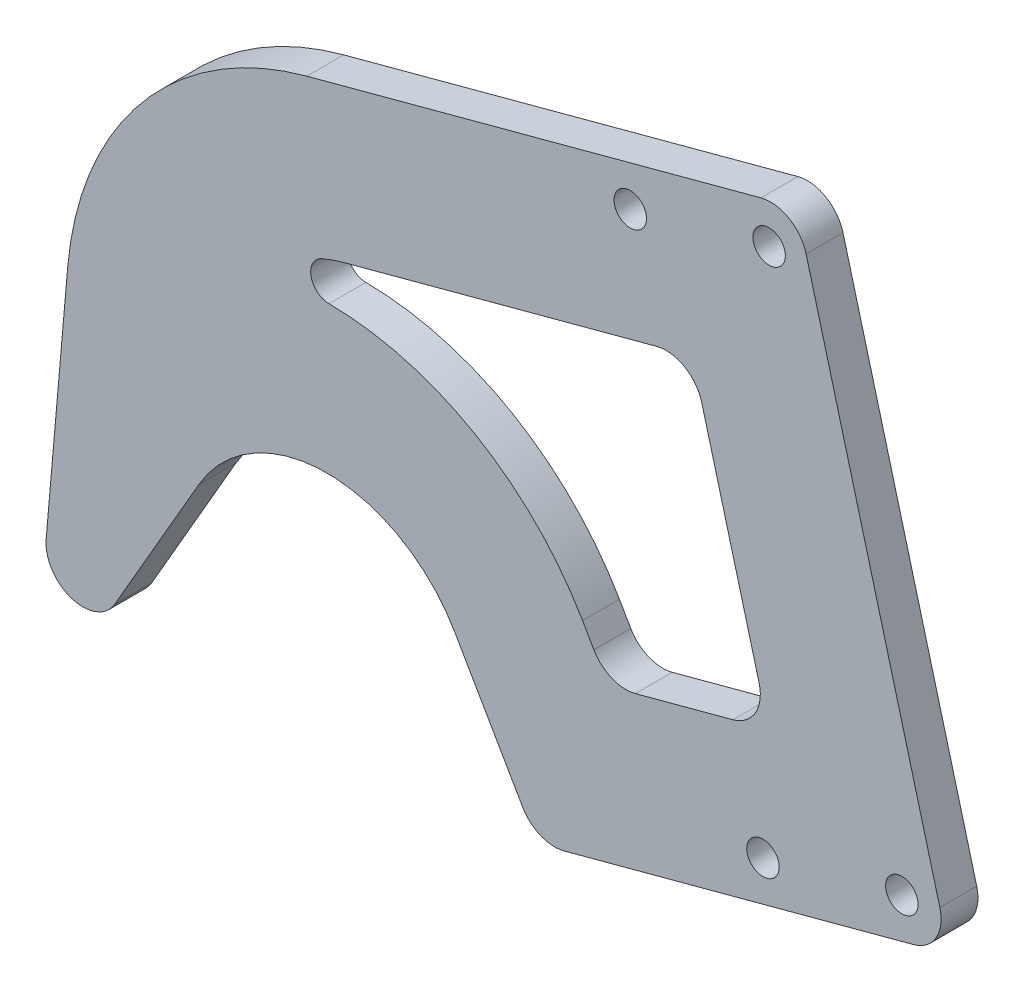
SolidWorks part; units mm, degrees
ref_plane "Front Plane" through (0, 0, 0) normal (0, 0, 1) x (1, 0, 0)
ref_plane "Top Plane" through (0, 0, 0) normal (0, 1, 0) x (1, 0, 0)
ref_plane "Right Plane" through (0, 0, 0) normal (1, 0, 0) x (0, 0, -1)
sketch "Sketch1" plane through (0, 0, 0) normal (0, 0, 1) x (1, 0, 0)
  line L0 (25.9858, -2.3029) -> (10.9985, 23.6559) construction
  line L1 (-10.9985, 23.6559) -> (-25.9858, -2.3029) construction
  line L2 (-14.9873, -21.3529) -> (14.9873, -21.3529) construction
  line L3 (-10.9985, 23.6559) -> (-18.2404, 11.1125)
  line L6 (-24.153, 12.9767) -> (-22.2978, 34.1822)
  line L12 (53.5592, 20.9251) -> (40.4112, 69.9942)
  line L14 (-1.7207, 58.705) -> (40.4112, 69.9942)
  line L15 (10.9985, 23.6559) -> (16.8478, 13.5246)
  line L18 (20.4192, 12.0453) -> (53.5592, 20.9251)
  line L24 (0, 0) -> (0, 91.0406) construction
  arc A0 (-10.9985, 23.6559) -> (10.9985, 23.6559) centre (0, 17.3059) cw construction
  arc A1 (25.9858, -2.3029) -> (14.9873, -21.3529) centre (14.9873, -8.6529) cw construction
  arc A3 (-25.9858, -2.3029) -> (-14.9873, -21.3529) centre (-14.9873, -8.6529) ccw construction
  arc A7 (-24.153, 12.9767) -> (-18.2404, 11.1125) centre (-20.9901, 12.7) ccw
  circle A8 centre (0, 0) radius 21.3529 construction
  arc A9 (-10.9985, 23.6559) -> (10.9985, 23.6559) centre (0, 17.3059) cw
  arc A11 (-1.7207, 58.705) -> (-22.2978, 34.1822) centre (5.5019, 31.75) ccw
  arc A13 (16.8478, 13.5246) -> (20.4192, 12.0453) centre (19.5974, 15.1121) ccw
  point P10 (0, 0)
  dimension "D2" = 12.7
  dimension "D1" = 3.175
  dimension "D6" = 57.15
  dimension "D7" = 31.75
  dimension "D9" = 6.35
  dimension "D3" = 29.9746
  dimension "D4" = 25
  dimension "D5" = 12.7
  dimension "D8" = 50.8
  dimension "D10" = 15
extrude "Boss-Extrude1" add sketch "Sketch1" along normal mid plane 3.175
sketch "Sketch3" plane through (0, 0, 1.5875) normal (0, 0, 1) x (1, 0, 0)
  line L20 (24.1919, 26.2042) -> (38.0049, 29.9054)
  line L21 (38.0049, 29.9054) -> (31.4309, 54.4399)
  line L24 (31.4309, 54.4399) -> (1.5663, 46.4377)
  line L27 (24.1919, 26.2042) -> (38.0049, 29.9054)
  line L28 (38.0049, 29.9054) -> (31.4309, 54.4399)
  line L31 (31.4309, 54.4399) -> (1.5663, 46.4377)
  line L68 (21.997, 30.0059) -> (24.1919, 26.2042)
  line L69 (21.997, 30.0059) -> (24.1919, 26.2042)
  arc A31 (21.997, 30.0059) -> (-5.6705, 42.0648) centre (0, 17.3059) ccw
  arc A32 (21.997, 30.0059) -> (-5.6705, 42.0648) centre (0, 17.3059) ccw
  arc A36 (1.5663, 46.4377) -> (-5.6705, 42.0648) centre (5.5019, 31.75) ccw
  arc A37 (1.5663, 46.4377) -> (-5.6705, 42.0648) centre (5.5019, 31.75) ccw
  point P2 (-4.0779, 39.1535)
  point P5 (0, 0)
  dimension "D1" = 12.7
extrude "Cut-Extrude2" cut sketch "Sketch3" against normal through all
sketch "Sketch6" plane through (0, 0, -1.5875) normal (0, 0, -1) x (-1, 0, 0)
  circle A0 centre (-37.5201, 20.0854) radius 1.397 construction
  circle A1 centre (-26.101, 62.7019) radius 1.397 construction
  circle A2 centre (-38.0493, 65.9034) radius 1.397 construction
  circle A3 centre (-49.4684, 23.2869) radius 1.397 construction
  circle A4 centre (-37.5201, 20.0854) radius 1.397
  circle A5 centre (-26.101, 62.7019) radius 1.397
  circle A6 centre (-38.0493, 65.9034) radius 1.397
  circle A7 centre (-49.4684, 23.2869) radius 1.397
extrude "Cut-Extrude4" cut sketch "Sketch6" against normal through all
fillet "Fillet2" radius 3.175 5 edges at (31.4309, 54.4399, 0) (38.0049, 29.9054, 0) (24.1919, 26.2042, 0) (53.5592, 20.9251, 0) (40.4112, 69.9942, 0)
fillet "Fillet3" radius 1.5875 1 edges at (-5.6705, 42.0648, 0)
